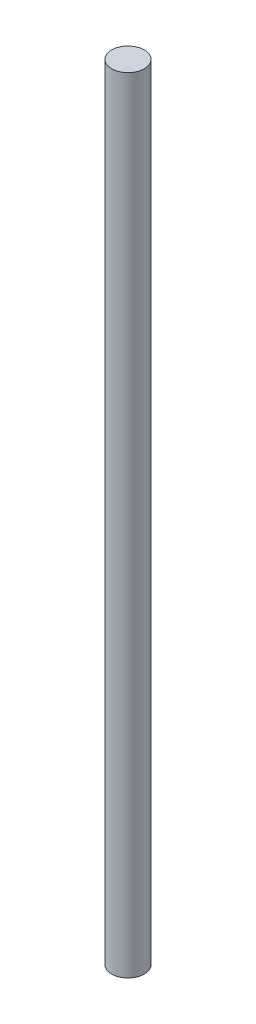
SolidWorks part; units mm, degrees
ref_plane "Front Plane" through (0, 0, 0) normal (0, 0, 1) x (1, 0, 0)
ref_plane "Top Plane" through (0, 0, 0) normal (0, 1, 0) x (1, 0, 0)
ref_plane "Right Plane" through (0, 0, 0) normal (1, 0, 0) x (0, 0, -1)
sketch "Sketch1" plane through (0, 0, 0) normal (0, 1, 0) x (1, 0, 0)
  circle A0 centre (0, 0) radius 0.5
extrude "Boss-Extrude1" add sketch "Sketch1" along normal blind 24
